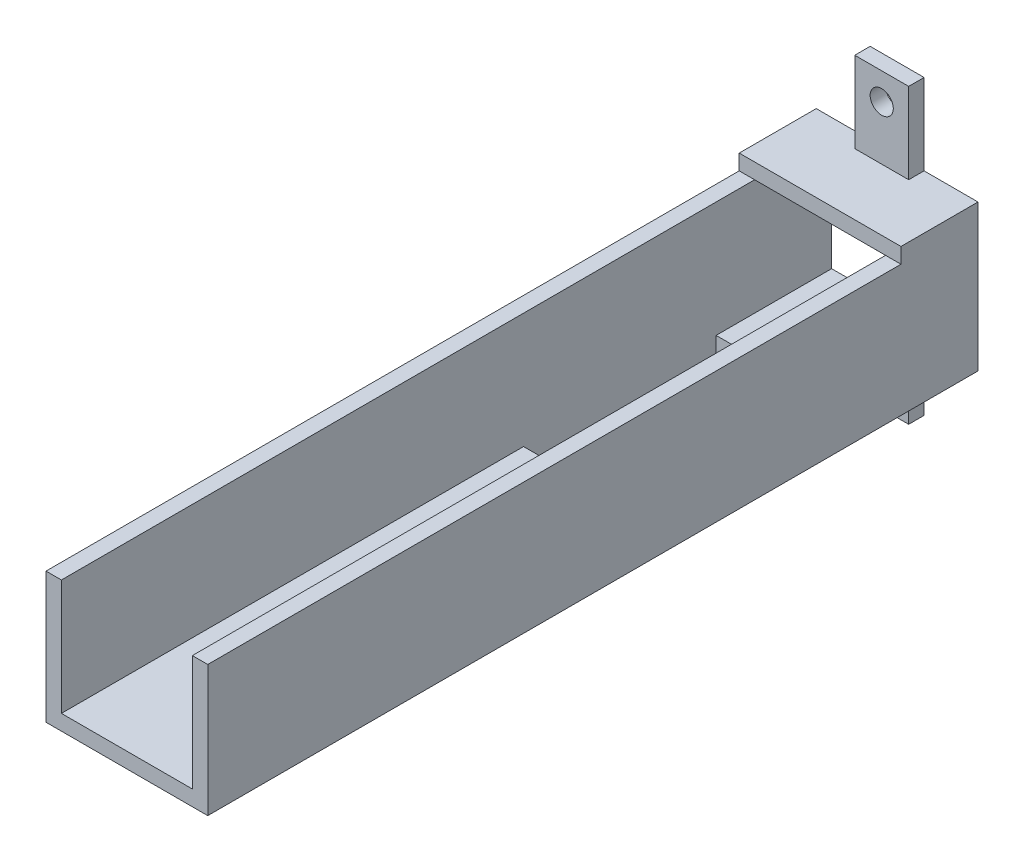
SolidWorks part; units mm, degrees
ref_plane "Спереди" through (0, 0, 0) normal (0, 0, 1) x (1, 0, 0)
ref_plane "Сверху" through (0, 0, 0) normal (0, 1, 0) x (1, 0, 0)
ref_plane "Справа" through (0, 0, 0) normal (1, 0, 0) x (0, 0, -1)
sketch "Эскиз1" plane through (0, 0, 0) normal (0, 0, 1) x (1, 0, 0)
  line L0 (0, 0) -> (-8.5, 0)
  line L1 (-8.5, 0) -> (-8.5, 15)
  line L2 (-8.5, 15) -> (-10.5, 15)
  line L3 (-10.5, 15) -> (-10.5, -2)
  line L4 (-10.5, -2) -> (10.5, -2)
  line L5 (10.5, -2) -> (10.5, 15)
  line L6 (10.5, 15) -> (8.5, 15)
  line L7 (8.5, 15) -> (8.5, 0)
  line L8 (8.5, 0) -> (0, 0)
extrude "Бобышка-Вытянуть1" add sketch "Эскиз1" along normal blind 100
sketch "Эскиз2" plane through (0, 0, 0) normal (0, 1, 0) x (1, 0, 0)
  line L1 (0, -15) -> (-8.5, -15)
  line L2 (-8.5, -100) -> (-8.5, 0) construction
  line L3 (-8.5, -15) -> (-8.5, -40)
  line L4 (-8.5, -40) -> (8.5, -40)
  line L5 (8.5, -100) -> (8.5, 0) construction
  line L6 (8.5, -40) -> (8.5, -15)
  line L7 (8.5, -100) -> (8.5, 0) construction
  line L8 (8.5, -15) -> (0, -15)
extrude "Вырез-Вытянуть1" cut sketch "Эскиз2" against normal through all
sketch "Эскиз3" plane through (0, 0, 0) normal (0, 0, -1) x (-1, 0, 0)
  line L0 (-10.5, 15) -> (-10.5, 17)
  line L1 (10.5, 15) -> (10.5, 17)
  line L2 (10.5, 17) -> (-10.5, 17)
  line L3 (-10.5, 15) -> (10.5, 15)
extrude "Бобышка-Вытянуть2" add sketch "Эскиз3" against normal blind 10
sketch "Эскиз4" plane through (0, 0, 0) normal (0, 0, -1) x (-1, 0, 0)
  line L0 (-3.5, 27.5) -> (3.5, 27.5)
  line L2 (10.5, 17) -> (-10.5, 17) construction
  line L3 (0, 17) -> (-3.5, 17)
  line L4 (-3.5, 17) -> (-3.5, 20.5)
  line L6 (3.5, 20.5) -> (3.5, 17)
  line L7 (3.5, 17) -> (0, 17)
  line L8 (3.5, 20.5) -> (3.5, 27.5)
  line L10 (-3.5, 27.5) -> (-3.5, 20.5)
  line L11 (3.5, -3.5) -> (3.5, -10.5)
  line L12 (10.5, -2) -> (-10.5, -2) construction
  line L13 (0, -2) -> (-3.5, -2)
  line L14 (-3.5, -2) -> (-3.5, -3.5)
  line L19 (3.5, -3.5) -> (3.5, -2)
  line L20 (3.5, -2) -> (0, -2)
  line L21 (3.5, -10.5) -> (-3.5, -10.5)
  line L22 (-3.5, -10.5) -> (-3.5, -3.5)
  circle A2 centre (0, 24) radius 1.5
  circle A3 centre (0, -7) radius 1.5
extrude "Бобышка-Вытянуть3" add sketch "Эскиз4" against normal blind 2
